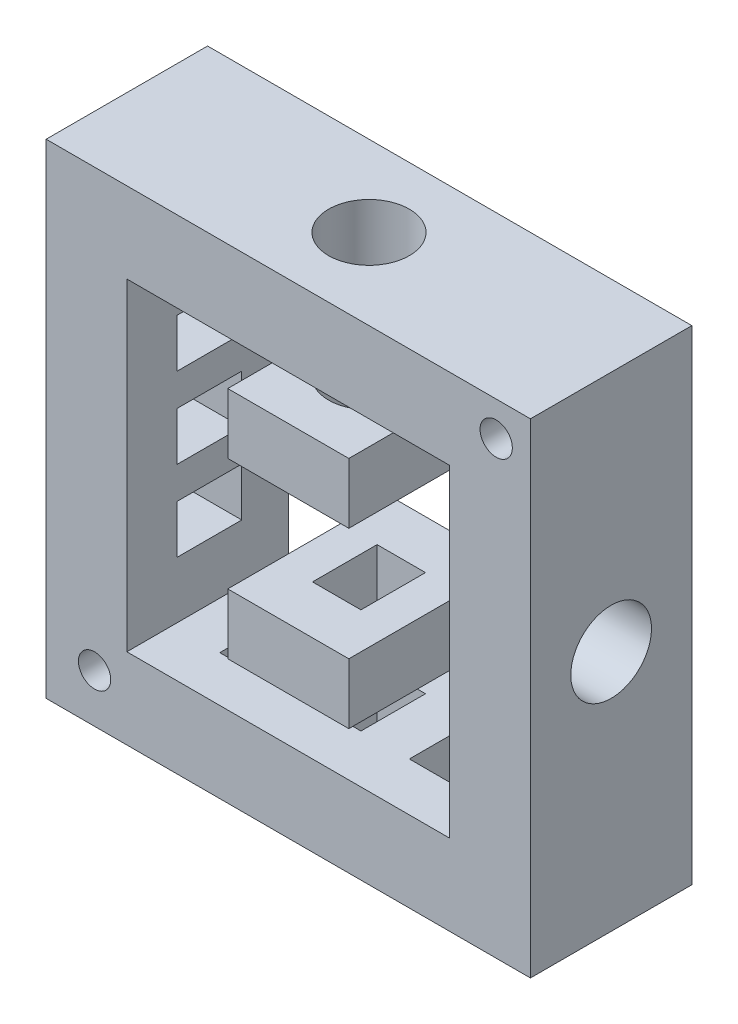
SolidWorks part; units mm, degrees
ref_plane "Front Plane" through (0, 0, 0) normal (0, 0, 1) x (1, 0, 0)
ref_plane "Top Plane" through (0, 0, 0) normal (0, 1, 0) x (1, 0, 0)
ref_plane "Right Plane" through (0, 0, 0) normal (1, 0, 0) x (0, 0, -1)
sketch "Sketch1" plane through (0, 0, 0) normal (0, 0, 1) x (1, 0, 0)
  line L1 (-15, 15) -> (15, 15)
  line L2 (-15, 15) -> (-15, -15)
  line L3 (-15, -15) -> (15, -15)
  line L4 (15, 15) -> (15, -15)
  line L5 (-15, 15) -> (15, -15) construction
  line L6 (-15, -15) -> (15, 15) construction
  point P0 (0, 0)
  dimension "D1" = 30
  dimension "D2" = 30
extrude "Boss-Extrude1" add sketch "Sketch1" along normal blind 10
sketch "Sketch2" plane through (0, 0, 10) normal (0, 0, 1) x (1, 0, 0)
  line L1 (-15, 15) -> (15, 15)
  line L2 (-15, 15) -> (-15, -15)
  line L3 (-15, -15) -> (15, -15)
  line L4 (15, 15) -> (15, -15)
  line L5 (-15, 15) -> (15, -15) construction
  line L6 (-15, -15) -> (15, 15) construction
  line L7 (10, 10) -> (-10, 10)
  line L8 (10, 10) -> (10, -10)
  line L9 (10, -10) -> (-10, -10)
  line L10 (-10, 10) -> (-10, -10)
  line L11 (10, 10) -> (-10, -10) construction
  line L12 (10, -10) -> (-10, 10) construction
  line L13 (0, 0) -> (0, -3.5) construction
  line L14 (0, 0) -> (0, 3.5) construction
  line L15 (-3.75, 7.2488) -> (3.75, 7.2488)
  line L16 (-3.75, 7.2488) -> (-3.75, -7.2488)
  line L17 (-3.75, -7.2488) -> (3.75, -7.2488)
  line L18 (3.75, 7.2488) -> (3.75, -7.2488)
  line L19 (-3.75, 7.2488) -> (3.75, -7.2488) construction
  line L20 (-3.75, -7.2488) -> (3.75, 7.2488) construction
  line L21 (-3.75, 3.5) -> (3.75, 3.5)
  line L22 (-3.75, 3.5) -> (-3.75, -3.5)
  line L23 (-3.75, -3.5) -> (3.75, -3.5)
  line L24 (3.75, 3.5) -> (3.75, -3.5)
  line L25 (-3.75, 3.5) -> (3.75, -3.5) construction
  line L26 (-3.75, -3.5) -> (3.75, 3.5) construction
  point P0 (0, 0)
  point P7 (0, 0)
  line M18 (15, -15) -> (15, 15)
  line M19 (15, 15) -> (-15, 15)
  line M20 (-15, 15) -> (-15, -15)
  line M21 (-15, -15) -> (15, -15)
  dimension "D1" = 20
  dimension "D2" = 20
  dimension "D3" = 3.5
  dimension "D4" = 3.5
  dimension "D5" = 7
  dimension "D6" = 7.5
  dimension "D7" = 7.5
extrude "Boss-Extrude2" add sketch "Sketch2" along normal blind 10 separate body contours L10 L7 L8 L9 M21 M18 M19 M20 | L16 L21 L18 L15 | L23 L16 L17 L18
sketch "Sketch3" plane through (0, 0, 20) normal (0, 0, 1) x (1, 0, 0)
  line L1 (-15, 15) -> (15, 15)
  line L2 (-15, 15) -> (-15, -15)
  line L3 (-15, -15) -> (15, -15)
  line L4 (15, 15) -> (15, -15)
extrude "Boss-Extrude3" add sketch "Sketch3" along normal blind 10 separate body
sketch "Sketch4" plane through (0, 0, 30) normal (0, 0, 1) x (1, 0, 0)
  line L1 (-15, 15) -> (-15, -15) construction
  line L3 (-15, 0) -> (-6, 0) construction
  circle A0 centre (-6, 0) radius 3.1
  dimension "D1" = 9
sketch "Sketch5" plane through (0, 0, 0) normal (0, 0, -1) x (-1, 0, 0)
  line L0 (-15, -0.3729) -> (-6, -0.3729) construction
  line L1 (-15, -15) -> (-15, 15) construction
  circle A0 centre (-6, -0.3729) radius 3.1
  dimension "D1" = 9
extrude "Cut-Extrude1" cut sketch "Sketch4" against normal blind 10
extrude "Cut-Extrude2" cut sketch "Sketch5" against normal blind 10 contours A0
sketch "Sketch8" plane through (0, 0, 30) normal (0, 0, 1) x (1, 0, 0)
  line L0 (-15, -15) -> (-12, -12) construction
  line L1 (-15, -15) -> (15, -15) construction
  line L2 (15, 15) -> (12.8787, 12.8787) construction
  line L3 (15, 15) -> (-15, 15) construction
  circle A0 centre (-12, -12) radius 1
  circle A1 centre (12.8787, 12.8787) radius 1
  dimension "D1" = 3
  dimension "D2" = 45
  dimension "D3" = 3
  dimension "D4" = 45
extrude "Cut-Extrude3" cut sketch "Sketch8" against normal up to surface (30 mm away)
delete or keep bodies "Body-Delete/Keep 1" type delete bodies bodies 111 112
sketch "Sketch9" plane through (0, 15, 0) normal (0, 1, 0) x (1, 0, 0)
  line L0 (15, -15) -> (-15, -15) construction
  line L1 (15, -20) -> (15, -10) construction
  line L2 (-15, -20) -> (-15, -10) construction
  circle A0 centre (0, -15) radius 2.5
extrude "Cut-Extrude5" cut sketch "Sketch9" against normal up to surface (11.5 mm away)
sketch "Sketch10" plane through (15, 0, 0) normal (1, 0, 0) x (0, 0, -1)
  line L0 (-15, 15) -> (-15, -49985) construction
  line L1 (-20, 15) -> (-10, 15) construction
  line L2 (-20, -15) -> (-10, -15) construction
  circle A0 centre (-15, 0) radius 2.5
  point P4 (-15, 15)
  point P7 (-15, -15)
extrude "Cut-Extrude6" cut sketch "Sketch10" against normal blind 10
sketch "Sketch11" plane through (-15, 0, 0) normal (-1, 0, 0) x (0, 0, 1)
  line L8 (10, 0) -> (14.8835, 0) construction
  line L9 (10, 15) -> (10, -15) construction
  line L29 (12.8835, 3.5) -> (12.8835, 6.5)
  line L30 (12.8835, -1.5) -> (16.8835, -1.5)
  line L31 (12.8835, -1.5) -> (12.8835, 1.5)
  line L32 (12.8835, 1.5) -> (16.8835, 1.5)
  line L33 (16.8835, -1.5) -> (16.8835, 1.5)
  line L34 (12.8835, -1.5) -> (16.8835, 1.5) construction
  line L35 (12.8835, 1.5) -> (16.8835, -1.5) construction
  line L36 (12.8835, 3.5) -> (16.8835, 3.5)
  line L37 (16.8835, 3.5) -> (16.8835, 6.5)
  line L38 (12.8835, 6.5) -> (16.8835, 6.5)
  line L47 (12.8835, -1.4929) -> (12.8835, 1.5071)
  line L48 (12.8835, -1.4929) -> (16.8835, -1.4929)
  line L49 (16.8835, -1.4929) -> (16.8835, 1.5071)
  line L50 (12.8835, 1.5071) -> (16.8835, 1.5071)
  line L51 (12.8835, 3.5071) -> (12.8835, 6.5071)
  line L52 (12.8835, 3.5071) -> (16.8835, 3.5071)
  line L53 (16.8835, 3.5071) -> (16.8835, 6.5071)
  line L54 (12.8835, 6.5071) -> (16.8835, 6.5071)
  line L59 (12.8835, -6.4858) -> (12.8835, -3.4858)
  line L60 (12.8835, -6.4858) -> (16.8835, -6.4858)
  line L61 (16.8835, -6.4858) -> (16.8835, -3.4858)
  line L62 (12.8835, -3.4858) -> (16.8835, -3.4858)
  line L63 (12.8835, -1.4858) -> (12.8835, 1.5142)
  line L64 (12.8835, -1.4858) -> (16.8835, -1.4858)
  line L65 (16.8835, -1.4858) -> (16.8835, 1.5142)
  line L66 (12.8835, 1.5142) -> (16.8835, 1.5142)
  line L67 (12.8835, 3.5142) -> (12.8835, 6.5142)
  line L68 (12.8835, 3.5142) -> (16.8835, 3.5142)
  line L69 (16.8835, 3.5142) -> (16.8835, 6.5142)
  line L70 (12.8835, 6.5142) -> (16.8835, 6.5142)
  line L71 (12.8835, -6.4929) -> (12.8835, -3.4929)
  line L72 (12.8835, -6.4929) -> (16.8835, -6.4929)
  line L73 (16.8835, -6.4929) -> (16.8835, -3.4929)
  line L74 (12.8835, -3.4929) -> (16.8835, -3.4929)
  line L79 (12.8835, -1.5) -> (12.8835, 3.5) construction
  line L80 (12.8835, 13.5) -> (12.8835, 16.5) [skipped]
  line L81 (12.8835, 16.5) -> (16.8835, 16.5) [skipped]
  line L82 (16.8835, 13.5) -> (16.8835, 16.5) [skipped]
  line L83 (12.8835, 13.5) -> (16.8835, 13.5) [skipped]
  line L84 (12.8835, 8.5) -> (12.8835, 11.5) [skipped]
  line L85 (12.8835, 11.5) -> (16.8835, 11.5) [skipped]
  line L86 (16.8835, 8.5) -> (16.8835, 11.5) [skipped]
  line L87 (12.8835, 8.5) -> (16.8835, 8.5) [skipped]
  line L88 (12.8835, -11.4858) -> (12.8835, -8.4858) [skipped]
  line L89 (12.8835, -8.4858) -> (16.8835, -8.4858) [skipped]
  line L90 (16.8835, -11.4858) -> (16.8835, -8.4858) [skipped]
  line L91 (12.8835, -11.4858) -> (16.8835, -11.4858) [skipped]
  line L92 (12.8835, 8.5071) -> (12.8835, 11.5071) [skipped]
  line L93 (12.8835, 11.5071) -> (16.8835, 11.5071) [skipped]
  line L94 (16.8835, 8.5071) -> (16.8835, 11.5071) [skipped]
  line L95 (12.8835, 8.5071) -> (16.8835, 8.5071) [skipped]
  point P6 (15.9943, 0.4272)
  dimension "D3" = 4
  dimension "D4" = 3
  dimension "D5" = 5
  dimension "D1" = 3
  dimension "D2" = 4
extrude "Cut-Extrude7" cut sketch "Sketch11" against normal blind 9
sketch "Sketch13" plane through (0, -15, 0) normal (0, -1, 0) x (1, 0, 0)
  line L0 (15, 15) -> (-15, 15) construction
  line L1 (15, 20) -> (15, 10) construction
  line L2 (-15, 20) -> (-15, 10) construction
  line L3 (0, 15) -> (0, 10) construction
  line L4 (-15, 10) -> (15, 10) construction
  line L5 (7.5, 13) -> (7.5, 17)
  line L6 (1.5, 13) -> (-1.5, 13)
  line L7 (1.5, 13) -> (1.5, 17)
  line L8 (1.5, 17) -> (-1.5, 17)
  line L9 (-1.5, 13) -> (-1.5, 17)
  line L10 (1.5, 13) -> (-1.5, 17) construction
  line L11 (1.5, 17) -> (-1.5, 13) construction
  line L12 (7.5, 13) -> (4.5, 13)
  line L13 (4.5, 13) -> (4.5, 17)
  line L14 (7.5, 17) -> (4.5, 17)
  line L19 (-4.0767, 13.1667) -> (-4.0767, 17.1667)
  line L20 (-4.0767, 13.1667) -> (-7.0767, 13.1667)
  line L21 (-7.0767, 13.1667) -> (-7.0767, 17.1667)
  line L22 (-4.0767, 17.1667) -> (-7.0767, 17.1667)
  line L43 (1.5, 13) -> (7.5, 13) construction
  line L44 (-21.6533, 13.3334) -> (-21.6533, 17.3334) [skipped]
  line L45 (-21.6533, 17.3334) -> (-24.6533, 17.3334) [skipped]
  line L46 (-24.6533, 13.3334) -> (-24.6533, 17.3334) [skipped]
  line L47 (-21.6533, 13.3334) -> (-24.6533, 13.3334) [skipped]
  line L48 (-15.6533, 13.3334) -> (-15.6533, 17.3334) [skipped]
  line L49 (-15.6533, 17.3334) -> (-18.6533, 17.3334) [skipped]
  line L50 (-18.6533, 13.3334) -> (-18.6533, 17.3334) [skipped]
  line L51 (-15.6533, 13.3334) -> (-18.6533, 13.3334) [skipped]
  line L52 (-9.6533, 13.3334) -> (-9.6533, 17.3334) [skipped]
  line L53 (-9.6533, 17.3334) -> (-12.6533, 17.3334) [skipped]
  line L54 (-12.6533, 13.3334) -> (-12.6533, 17.3334) [skipped]
  line L55 (-9.6533, 13.3334) -> (-12.6533, 13.3334) [skipped]
  line L56 (13.5, 13) -> (13.5, 17) [skipped]
  line L57 (13.5, 17) -> (10.5, 17) [skipped]
  line L58 (10.5, 13) -> (10.5, 17) [skipped]
  line L59 (13.5, 13) -> (10.5, 13) [skipped]
  line L60 (-10.0767, 13.1667) -> (-10.0767, 17.1667) [skipped]
  line L61 (-10.0767, 17.1667) -> (-13.0767, 17.1667) [skipped]
  line L62 (-13.0767, 13.1667) -> (-13.0767, 17.1667) [skipped]
  line L63 (-10.0767, 13.1667) -> (-13.0767, 13.1667) [skipped]
  line L64 (1.9233, 13.1667) -> (1.9233, 17.1667) [skipped]
  line L65 (1.9233, 17.1667) -> (-1.0767, 17.1667) [skipped]
  line L66 (-1.0767, 13.1667) -> (-1.0767, 17.1667) [skipped]
  line L67 (1.9233, 13.1667) -> (-1.0767, 13.1667) [skipped]
  dimension "D1" = 3
  dimension "D2" = 4
  dimension "D5" = 6
  dimension "D3" = 3
  dimension "D4" = 3
extrude "Cut-Extrude9" cut sketch "Sketch13" against normal blind 13 contours L9 L6 L7 L8 | L5 L14 L13 L12 | L19 L22 L21 L20
